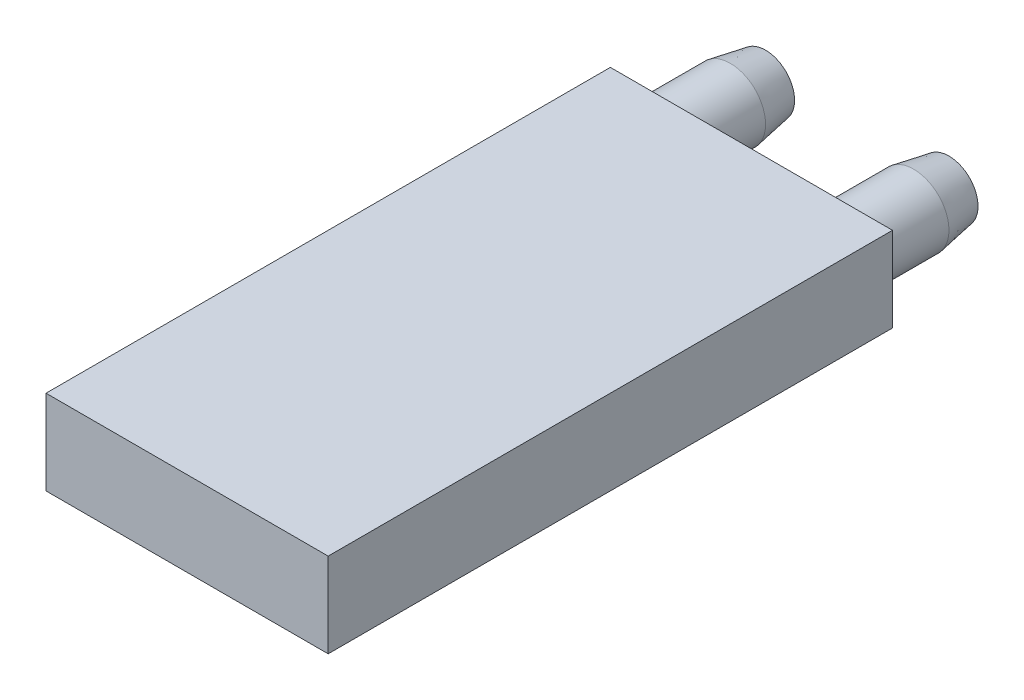
SolidWorks part; units mm, degrees
ref_plane "Front Plane" through (0, 0, 0) normal (0, 0, 1) x (1, 0, 0)
ref_plane "Top Plane" through (0, 0, 0) normal (0, 1, 0) x (1, 0, 0)
ref_plane "Right Plane" through (0, 0, 0) normal (1, 0, 0) x (0, 0, -1)
sketch "Sketch1" plane through (0, 0, 0) normal (0, 1, 0) x (1, 0, 0)
  line L1 (-20, 40) -> (20, 40)
  line L2 (-20, 40) -> (-20, -40)
  line L3 (-20, -40) -> (20, -40)
  line L4 (20, 40) -> (20, -40)
  line L5 (-20, 40) -> (20, -40) construction
  line L6 (-20, -40) -> (20, 40) construction
  point P0 (0, 0)
  dimension "D1" = 80
  dimension "D2" = 40
extrude "Boss-Extrude1" add sketch "Sketch1" along normal mid plane 12
sketch "Sketch2" plane through (0, 0, -40) normal (0, 0, -1) x (-1, 0, 0)
  line L0 (0, 0) -> (13, 0) construction
  line L1 (0, 0) -> (0, 6) construction
  line L2 (-20, 6) -> (20, 6) construction
  circle A0 centre (13, 0) radius 5
  circle A1 centre (-13, 0) radius 5
  point P9 (0, 0)
  dimension "D1" = 10
  dimension "D2" = 26
extrude "Boss-Extrude2" add sketch "Sketch2" along normal blind 15
chamfer "Chamfer1" distance 5 angle 10 2 edges at (-18, 0, -55) (18, 0, -55)
